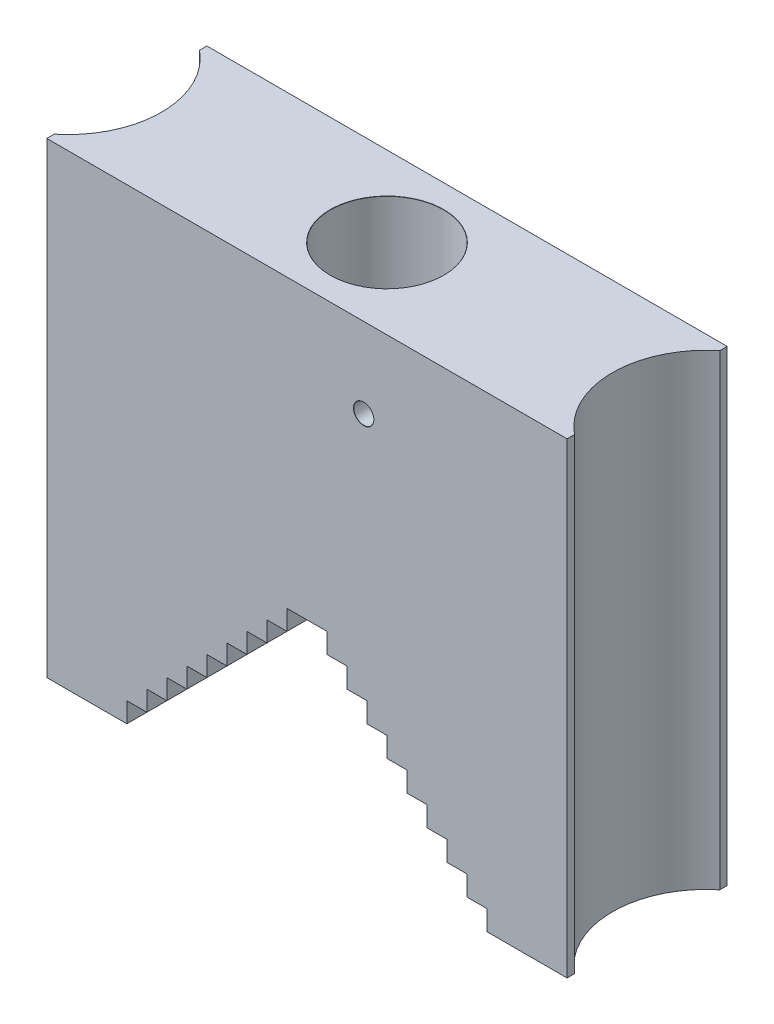
SolidWorks part; units mm, degrees
ref_plane "Front Plane" through (0, 0, 0) normal (0, 0, 1) x (1, 0, 0)
ref_plane "Top Plane" through (0, 0, 0) normal (0, 1, 0) x (1, 0, 0)
ref_plane "Right Plane" through (0, 0, 0) normal (1, 0, 0) x (0, 0, -1)
sketch "Sketch1" plane through (0, 0, 0) normal (0, 0, 1) x (1, 0, 0)
  line L1 (-39, -35) -> (39, -35)
  line L2 (-39, -35) -> (-39, 35)
  line L3 (-39, 35) -> (39, 35)
  line L4 (39, -35) -> (39, 35)
  line L5 (-39, -35) -> (39, 35) construction
  line L6 (-39, 35) -> (39, -35) construction
  point P0 (0, 0)
  dimension "D1" = 78
  dimension "D2" = 70
extrude "Boss-Extrude1" add sketch "Sketch1" along normal mid plane 24
hole_wizard "Ø17.0 (17) Diameter Hole1" positions "Sketch6" profile "Sketch7" hole size "Ø17.0" standard "ISO"
sketch "Sketch6" plane through (0, 35, 0) normal (0, 1, 0) x (1, 0, 0)
  point P0 (0, 0)
sketch "Sketch7" plane through (0, 35, 0) normal (1, 0, 0) x (0, 0, 1)
  line L0 (0, 0) -> (0, 30.1073)
  line L1 (0, 30.1073) -> (8.5, 25)
  line L2 (8.5, 25) -> (8.5, 0.025)
  line L3 (8.5, 0.025) -> (8.525, 0)
  line L5 (8.525, 0) -> (0, 0)
  line L6 (-8.5, 0.025) -> (-8.525, 0) construction
  line L10 (0, 30.1073) -> (-8.5, 25) construction
  line L11 (0, -6.35) -> (0, 107.95) construction
  dimension "Hole Dia." = 17
  dimension "Hole Depth" = 25
  dimension "Near C'Sink Dia." = 17.05
  dimension "Near C'Sink Angle" = 90
  dimension "Drill Angle" = 118
hole_wizard "Ø3.0 (3) Diameter Hole2" positions "Sketch9" profile "Sketch10" hole size "Ø3.0" standard "ISO" end condition through all
sketch "Sketch9" plane through (0, 0, 12) normal (0, 0, 1) x (1, 0, 0)
  line L0 (39, 35) -> (-39, 35) construction
  point P0 (8.5, 23)
  point P8 (39, 35)
  point P15 (11.8869, 18.7251)
  dimension "D1" = 8.5
  dimension "D2" = 12
sketch "Sketch10" plane through (8.5, 23, 12) normal (1, 0, 0) x (0, -1, 0)
  line L0 (0, 0) -> (0, 24)
  line L1 (0, 24) -> (1.5, 24)
  line L2 (1.5, 24) -> (1.5, 0.025)
  line L3 (1.5, 0.025) -> (1.525, 0)
  line L5 (1.525, 0) -> (0, 0)
  line L6 (-1.5, 0.025) -> (-1.525, 0) construction
  line L11 (0, -6.35) -> (0, 107.95) construction
  dimension "Thru Hole Dia." = 3
  dimension "Thru Hole Depth" = 24
  dimension "Near C'Sink Dia." = 3.05
  dimension "Near C'Sink Angle" = 90
sketch "Sketch11" plane through (0, 35, 0) normal (0, 1, 0) x (1, 0, 0)
  line L0 (0, 0) -> (0, 28.4767) construction
  line L1 (0, 0) -> (-47.8, 0) construction
  circle A0 centre (-47.8, 0) radius 14
  circle A1 centre (47.8, 0) radius 14
  dimension "D1" = 47.8
  dimension "D2" = 28
extrude "Cut-Extrude1" cut sketch "Sketch11" against normal up to next
sketch "Sketch12" plane through (0, 0, 12) normal (0, 0, 1) x (1, 0, 0)
  line L0 (-39, -35) -> (39, -35) construction
  line L1 (0, -8) -> (27, -35) construction
  line L2 (-27, -35) -> (27, -35) construction
  line L3 (0, -35) -> (0, -8) construction
  line L4 (-27, -8) -> (27, -8) construction
  line L5 (27, -35) -> (27, -8) construction
  line L6 (27, -8) -> (0, -35) construction
  line L7 (27, -35) -> (27, -32)
  line L8 (27, -32) -> (24, -32)
  line L9 (24, -32) -> (24, -29)
  line L10 (24, -29) -> (21, -29)
  line L11 (21, -29) -> (21, -26)
  line L12 (21, -26) -> (18, -26)
  line L13 (18, -26) -> (18, -23)
  line L14 (18, -23) -> (15, -23)
  line L15 (15, -23) -> (15, -20)
  line L16 (15, -20) -> (12, -20)
  line L17 (12, -20) -> (12, -17)
  line L18 (12, -17) -> (9, -17)
  line L19 (9, -17) -> (9, -14)
  line L20 (9, -14) -> (6, -14)
  line L21 (6, -14) -> (6, -11)
  line L22 (6, -11) -> (3, -11)
  line L23 (3, -11) -> (3, -8)
  line L24 (-27, -8) -> (0, -35) construction
  line L25 (-27, -35) -> (-27, -8) construction
  line L26 (0, -8) -> (-27, -35) construction
  line L27 (-3, -11) -> (-3, -8)
  line L28 (-6, -11) -> (-3, -11)
  line L29 (-6, -14) -> (-6, -11)
  line L30 (-9, -14) -> (-6, -14)
  line L31 (-9, -17) -> (-9, -14)
  line L32 (-12, -17) -> (-9, -17)
  line L33 (-12, -20) -> (-12, -17)
  line L34 (-15, -20) -> (-12, -20)
  line L35 (-15, -23) -> (-15, -20)
  line L36 (-18, -23) -> (-15, -23)
  line L37 (-18, -26) -> (-18, -23)
  line L38 (-21, -26) -> (-18, -26)
  line L39 (-21, -29) -> (-21, -26)
  line L40 (-24, -29) -> (-21, -29)
  line L41 (-24, -32) -> (-24, -29)
  line L42 (-27, -32) -> (-24, -32)
  line L43 (-27, -35) -> (-27, -32)
  line L44 (-3, -8) -> (3, -8)
  line L45 (-27, -35) -> (27, -35)
  dimension "D1" = 27
  dimension "D2" = 27
  dimension "D3" = 3
  dimension "D4" = 3
extrude "Cut-Extrude2" cut sketch "Sketch12" against normal up to next
